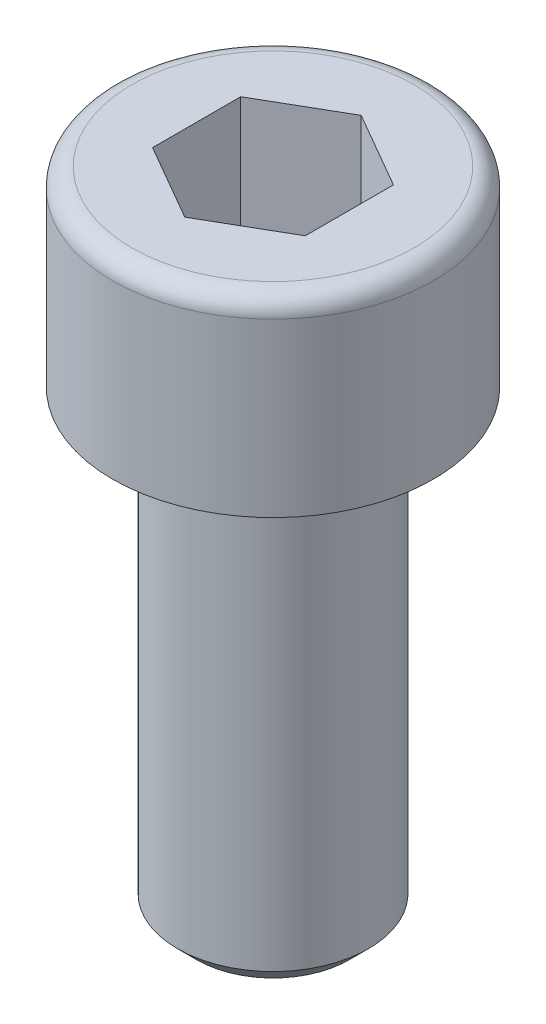
SolidWorks part; units mm, degrees
material "acero"
ref_plane "Alzado" through (0, 0, 0) normal (0, 0, 1) x (1, 0, 0)
ref_plane "Planta" through (0, 0, 0) normal (0, 1, 0) x (1, 0, 0)
ref_plane "Vista lateral" through (0, 0, 0) normal (1, 0, 0) x (0, 0, -1)
sketch "Croquis1" plane through (0, 0, 0) normal (0, 0, 1) x (1, 0, 0)
  line L0 (0, 0) -> (0, -60.9498) construction
  line L1 (0, 0) -> (4.2, 0)
  line L2 (4.2, 0) -> (4.2, -5)
  line L3 (4.2, -5) -> (2.5, -5)
  line L4 (2.5, -5) -> (2.5, -17)
  line L5 (2.5, -17) -> (0, -17)
  line L6 (0, -17) -> (0, 0)
  dimension "D1" = 12
  dimension "D2" = 5
  dimension "D3" = 8.4
  dimension "D4" = 5
revolve "Revolución1" add sketch "Croquis1" angle 360 about L0
sketch "Croquis2" plane through (0, 0, 0) normal (0, 1, 0) x (1, 0, 0)
  line L1 (2, 1.1547) -> (0, 2.3094)
  line L2 (0, 2.3094) -> (-2, 1.1547)
  line L3 (-2, 1.1547) -> (-2, -1.1547)
  line L4 (-2, -1.1547) -> (0, -2.3094)
  line L5 (0, -2.3094) -> (2, -1.1547)
  line L6 (2, -1.1547) -> (2, 1.1547)
  circle A0 centre (0, 0) radius 2 construction
  dimension "D1" = 4
extrude "Cortar-Extruir1" cut sketch "Croquis2" against normal blind 3
chamfer "Chaflán1" distance 0.5 angle 45 1 edges at (0, -17, 2.5)
fillet "Redondeo1" radius 0.5 1 edges at (0, 0, 4.2)
